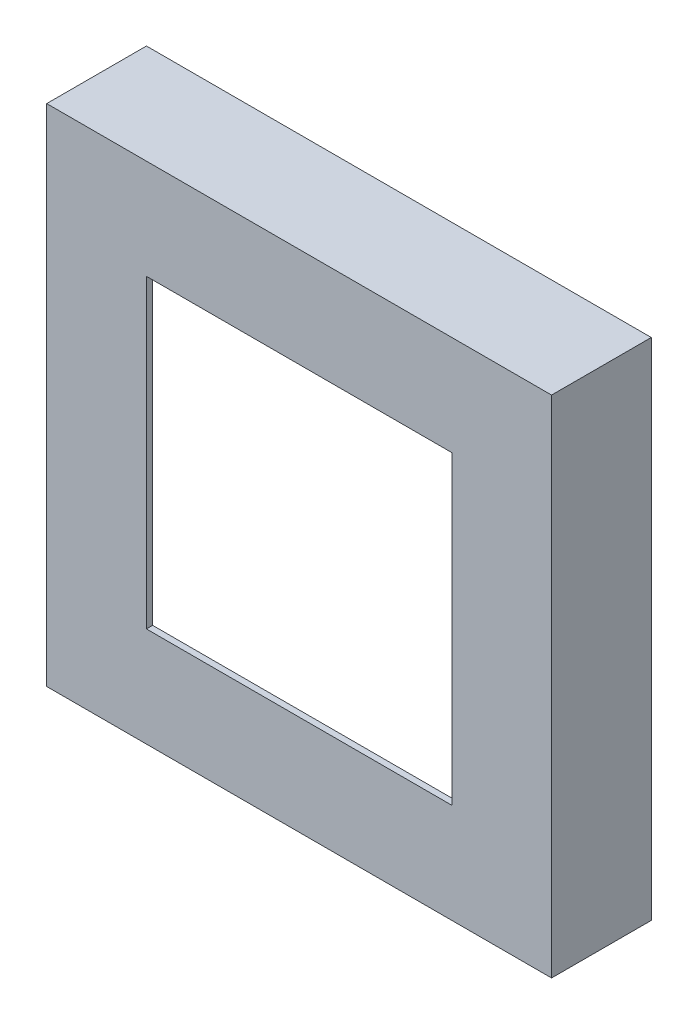
SolidWorks part; units mm, degrees
ref_plane "Front Plane" through (0, 0, 0) normal (0, 0, 1) x (1, 0, 0)
ref_plane "Top Plane" through (0, 0, 0) normal (0, 1, 0) x (1, 0, 0)
ref_plane "Right Plane" through (0, 0, 0) normal (1, 0, 0) x (0, 0, -1)
sketch "Sketch1" plane through (0, 0, 0) normal (0, 0, 1) x (1, 0, 0)
  line L0 (-1, -1) -> (-1, 80)
  line L1 (0, 0) -> (79, 0)
  line L2 (0, 0) -> (0, 79)
  line L3 (0, 79) -> (79, 79)
  line L4 (79, 0) -> (79, 79)
  line L5 (-1, 80) -> (80, 80)
  line L6 (80, -1) -> (80, 80)
  line L7 (-1, -1) -> (80, -1)
  dimension "D1" = 79
  dimension "D2" = 79
  dimension "D3" = 1
extrude "Boss-Extrude1" add sketch "Sketch1" along normal blind 15
sketch "Sketch2" plane through (0, 0, 15) normal (0, 0, 1) x (1, 0, 0)
  line L0 (-1, 80) -> (80, -1) construction
  line L1 (-1, 80) -> (80, 80)
  line L2 (-1, 80) -> (-1, -1)
  line L3 (-1, -1) -> (80, -1)
  line L4 (80, 80) -> (80, -1)
  line L5 (0, 79) -> (0, 0) construction
  line L6 (64, 15) -> (15, 15)
  line L7 (64, 15) -> (64, 64)
  line L8 (64, 64) -> (15, 64)
  line L9 (15, 15) -> (15, 64)
  line L10 (64, 15) -> (15, 64) construction
  line L11 (64, 64) -> (15, 15) construction
  point P6 (39.5, 39.5)
  dimension "D1" = 15
extrude "Boss-Extrude2" add sketch "Sketch2" along normal blind 1
